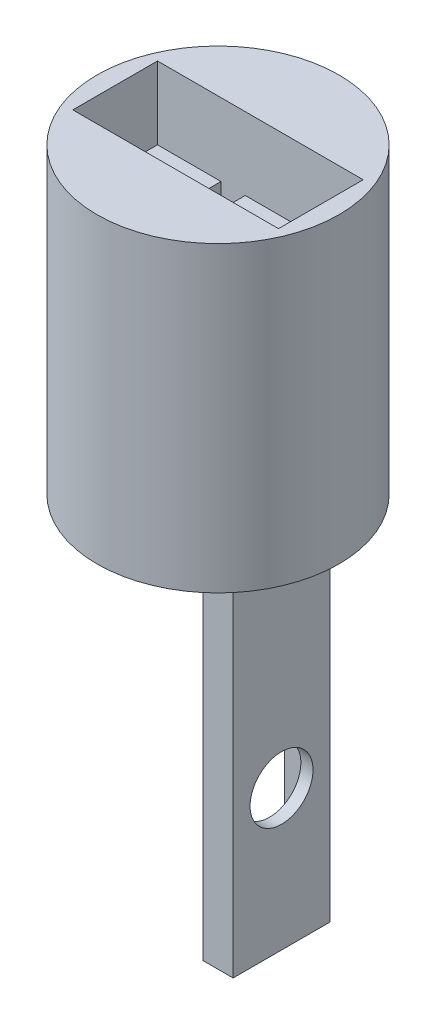
SolidWorks part; units mm, degrees
ref_plane "Front Plane" through (0, 0, 0) normal (0, 0, 1) x (1, 0, 0)
ref_plane "Top Plane" through (0, 0, 0) normal (0, 1, 0) x (1, 0, 0)
ref_plane "Right Plane" through (0, 0, 0) normal (1, 0, 0) x (0, 0, -1)
sketch "Sketch3" plane through (0, 0, 0) normal (0, 1, 0) x (1, 0, 0)
  circle A0 centre (0, 0) radius 10
  dimension "D1" = 20
extrude "Boss-Extrude1" add sketch "Sketch3" along normal blind 25
sketch "Sketch4" plane through (0, 0, 0) normal (0, -1, 0) x (-1, 0, 0)
  line L1 (-2.75, 4) -> (-5.25, 4)
  line L2 (-2.75, 4) -> (-2.75, -4)
  line L3 (-2.75, -4) -> (-5.25, -4)
  line L4 (-5.25, 4) -> (-5.25, -4)
  line L5 (-2.75, 4) -> (-5.25, -4) construction
  line L6 (-2.75, -4) -> (-5.25, 4) construction
  point P0 (-4, 0)
  point P5 (0, 0)
  dimension "D1" = 2.5
  dimension "D2" = 8
  dimension "D3" = 4
extrude "Boss-Extrude2" add sketch "Sketch4" along normal blind 30
sketch "Sketch5" plane through (5.25, 0, 0) normal (1, 0, 0) x (0, 0, -1)
  line L1 (4, 0) -> (-4, 0) construction
  circle A0 centre (0, -18.4) radius 2.6
  dimension "D1" = 5.2
  dimension "D2" = 18.4
extrude "Cut-Extrude1" cut sketch "Sketch5" against normal up to next
sketch "Sketch6" plane through (2.75, 0, 0) normal (-1, 0, 0) x (0, 0, 1)
  line L1 (-2.75, -29) -> (2.75, -29)
  line L2 (-2.75, -29) -> (-2.75, -7.8)
  line L3 (-2.75, -7.8) -> (2.75, -7.8)
  line L4 (2.75, -29) -> (2.75, -7.8)
  line L5 (-2.75, -29) -> (2.75, -7.8) construction
  line L6 (-2.75, -7.8) -> (2.75, -29) construction
  point P0 (0, -18.4)
  dimension "D1" = 21.2
  dimension "D2" = 5.5
extrude "Cut-Extrude2" cut sketch "Sketch6" against normal blind 1.5
sketch "Sketch7" plane through (0, 25, 0) normal (0, 1, 0) x (1, 0, 0)
  line L0 (-10, 0) -> (10, 0) construction
  line L1 (-8.5, -3.5) -> (8.5, -3.5)
  line L2 (-8.5, -3.5) -> (-8.5, 3.5)
  line L3 (-8.5, 3.5) -> (8.5, 3.5)
  line L4 (8.5, -3.5) -> (8.5, 3.5)
  circle A0 centre (0, 0) radius 10 construction
  point P4 (-8.5, 0)
  dimension "D1" = 7
  dimension "D2" = 17
  dimension "D3" = 1.5
extrude "Cut-Extrude3" cut sketch "Sketch7" against normal blind 6
sketch "Sketch8" plane through (0, 19, 0) normal (0, 1, 0) x (1, 0, 0)
  line L0 (8.5, 0) -> (-1.25, 0) construction
  line L1 (8.5, -3.5) -> (8.5, 3.5) construction
  line L2 (8.5, 3.5) -> (-8.5, 3.5) construction
  line L3 (-1.25, 3.5) -> (-3.25, 3.5)
  line L4 (-1.25, 3.5) -> (-1.25, -3.5)
  line L5 (-1.25, -3.5) -> (-3.25, -3.5)
  line L6 (-3.25, 3.5) -> (-3.25, -3.5)
  line L7 (-8.5, 3.5) -> (-8.5, -3.5) construction
  point P13 (0, 0)
  dimension "D1" = 9.75
  dimension "D2" = 2
extrude "Cut-Extrude4" cut sketch "Sketch8" against normal blind 4
